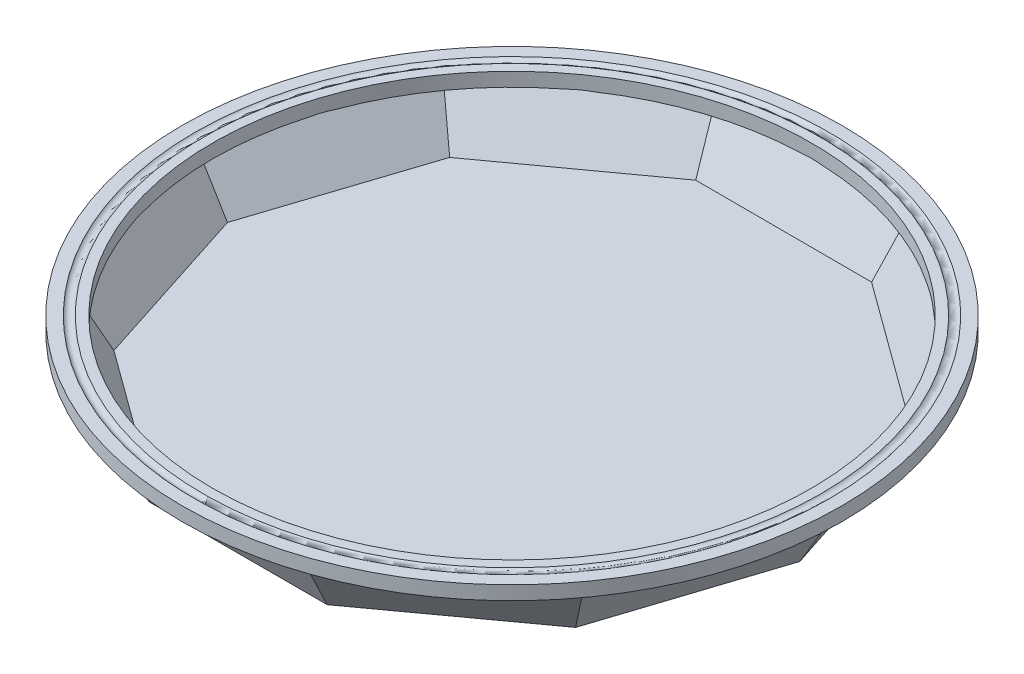
SolidWorks part; units mm, degrees
material "ABS"
ref_plane "Front Plane" through (0, 0, 0) normal (0, 0, 1) x (1, 0, 0)
ref_plane "Top Plane" through (0, 0, 0) normal (0, 1, 0) x (1, 0, 0)
ref_plane "Right Plane" through (0, 0, 0) normal (1, 0, 0) x (0, 0, -1)
sketch "Sketch4" plane through (0, 0, 0) normal (0, 1, 0) x (1, 0, 0)
  line L0 (38.6271, -118.8821) -> (101.1271, -73.4732)
  line L1 (125, 0) -> (101.1271, 73.4732)
  line L2 (101.1271, 73.4732) -> (38.6271, 118.8821)
  line L3 (38.6271, 118.8821) -> (-38.6271, 118.8821)
  line L4 (-38.6271, 118.8821) -> (-101.1271, 73.4732)
  line L5 (-101.1271, 73.4732) -> (-125, 0)
  line L6 (-125, 0) -> (-101.1271, -73.4732)
  line L7 (-101.1271, -73.4732) -> (-38.6271, -118.8821)
  line L8 (-38.6271, -118.8821) -> (38.6271, -118.8821)
  line L9 (101.1271, -73.4732) -> (125, 0)
  circle A0 centre (0, 0) radius 118.8821 construction
  dimension "D1" = 125
extrude "Stage1Ex" add sketch "Sketch4" along normal blind 30 draft 30 draft outward yes
sketch "Sketch7" plane through (0, 30, 0) normal (0, 1, 0) x (1, 0, 0)
  line L1 (-140.2233, 0.2614) -> (-113.5967, -82.2097)
  line L2 (-113.5967, -82.2097) -> (-43.58, -133.2795)
  line L3 (-43.58, -133.2795) -> (43.0827, -133.4411)
  line L4 (43.0827, -133.4411) -> (113.2893, -82.6327)
  line L5 (113.2893, -82.6327) -> (140.2233, -0.2614)
  line L6 (140.2233, -0.2614) -> (113.5967, 82.2097)
  line L7 (113.5967, 82.2097) -> (43.58, 133.2795)
  line L8 (43.58, 133.2795) -> (-43.0827, 133.4411)
  line L9 (-43.0827, 133.4411) -> (-113.2893, 82.6327)
  line L10 (-113.2893, 82.6327) -> (-140.2233, 0.2614)
  circle A0 centre (0, 0) radius 133.3605 construction
  dimension "D1" = 3
extrude "Stage1In" cut sketch "Sketch7" against normal blind 27 draft 30
sketch "Sketch8" plane through (0, 30, 0) normal (0, 1, 0) x (1, 0, 0)
  circle A0 centre (0, 0) radius 130
  circle A1 centre (0, 0) radius 143.2119
  dimension "D1" = 260
extrude "Boss-Extrude2" add sketch "Sketch8" against normal blind 6
sketch "Sketch14" plane through (0, 30, 0) normal (0, 1, 0) x (1, 0, 0)
  circle A0 centre (0, 0) radius 136
  dimension "D1" = 272
ref_plane "Plane1" through (0, 0, 0) normal (0.0019, 0, -1) x (-1, 0, -0.0019)
sketch "Sketch15" plane through (0, 0, 0) normal (0.0019, 0, -1) x (-1, 0, -0.0019)
  line L2 (136, 30) -> (-136, 30) construction
  circle A0 centre (-135.9725, 31.5) radius 2.38
  dimension "D1" = 4.76
  dimension "D2" = 1.5
sweep "Cut-Sweep1" cut profiles "Sketch15" path "Sketch14"
equation "\"GeneralThickness\"= 3"
equation "\"D2\"= \"GeneralThickness\""
equation "\"D1@Boss-Extrude2\"=\"GeneralThickness\"*2"
equation "\"BearBallRadio\"= 136"
equation "\"D1@Sketch14\"=\"BearBallRadio\"*2"
